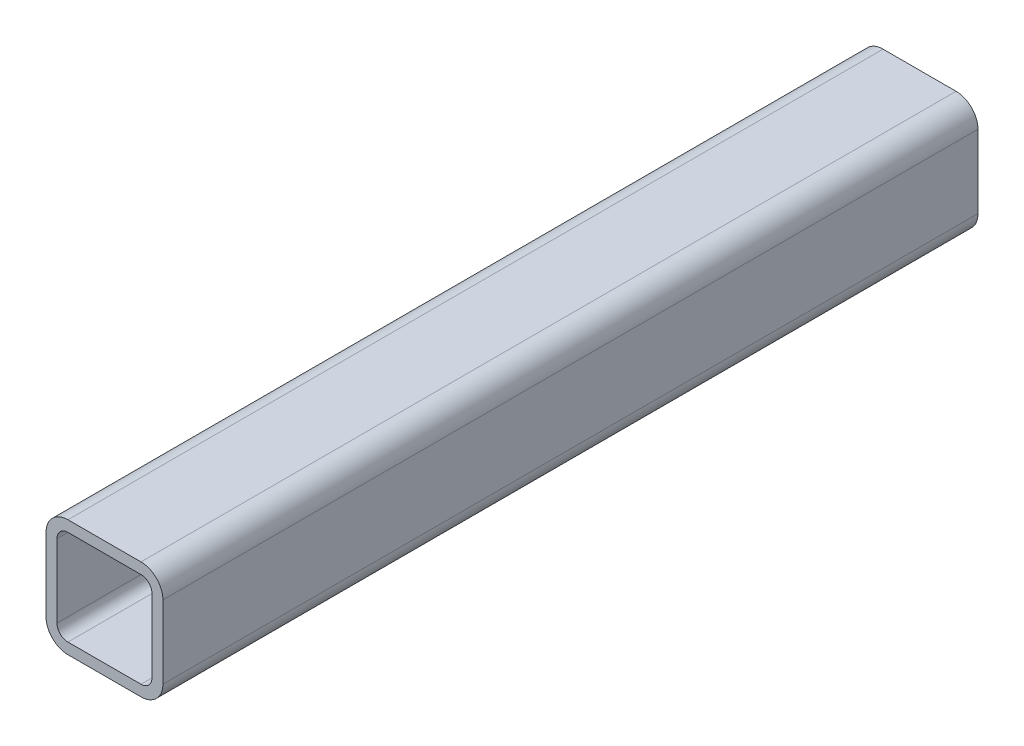
SolidWorks part; units mm, degrees
ref_plane "Płaszczyzna przednia" through (0, 0, 0) normal (0, 0, 1) x (1, 0, 0)
ref_plane "Płaszczyzna górna" through (0, 0, 0) normal (0, 1, 0) x (1, 0, 0)
ref_plane "Płaszczyzna prawa" through (0, 0, 0) normal (1, 0, 0) x (0, 0, -1)
sketch "Szkic1" plane through (0, 0, 0) normal (0, 0, 1) x (1, 0, 0)
  line L1 (9.53, 0) -> (41.27, 0)
  line L2 (0, 9.53) -> (0, 41.27)
  line L3 (9.53, 50.8) -> (41.27, 50.8)
  line L4 (50.8, 9.53) -> (50.8, 41.27)
  line L5 (9.52, 46.04) -> (41.28, 46.04)
  line L6 (4.76, 41.28) -> (4.76, 9.52)
  line L7 (9.52, 4.76) -> (41.28, 4.76)
  line L8 (46.04, 41.28) -> (46.04, 9.52)
  arc A0 (4.76, 9.52) -> (9.52, 4.76) centre (9.52, 9.52) ccw
  arc A1 (41.28, 4.76) -> (46.04, 9.52) centre (41.28, 9.52) ccw
  arc A2 (46.04, 41.28) -> (41.28, 46.04) centre (41.28, 41.28) ccw
  arc A3 (4.76, 41.28) -> (9.52, 46.04) centre (9.52, 41.28) cw
  arc A4 (41.27, 50.8) -> (50.8, 41.27) centre (41.27, 41.27) cw
  arc A5 (50.8, 9.53) -> (41.27, 0) centre (41.27, 9.53) cw
  arc A6 (9.53, 0) -> (0, 9.53) centre (9.53, 9.53) cw
  arc A7 (0, 41.27) -> (9.53, 50.8) centre (9.53, 41.27) cw
  dimension "D7" = 4.76
  dimension "D8" = 9.53
  dimension "D1" = 50.8
  dimension "D2" = 50.8
  dimension "D3" = 41.28
  dimension "D4" = 41.28
  dimension "D5" = 4.76
  dimension "D6" = 4.76
extrude "Dodanie-wyciągnięcie1" add sketch "Szkic1" along normal blind 354.2
